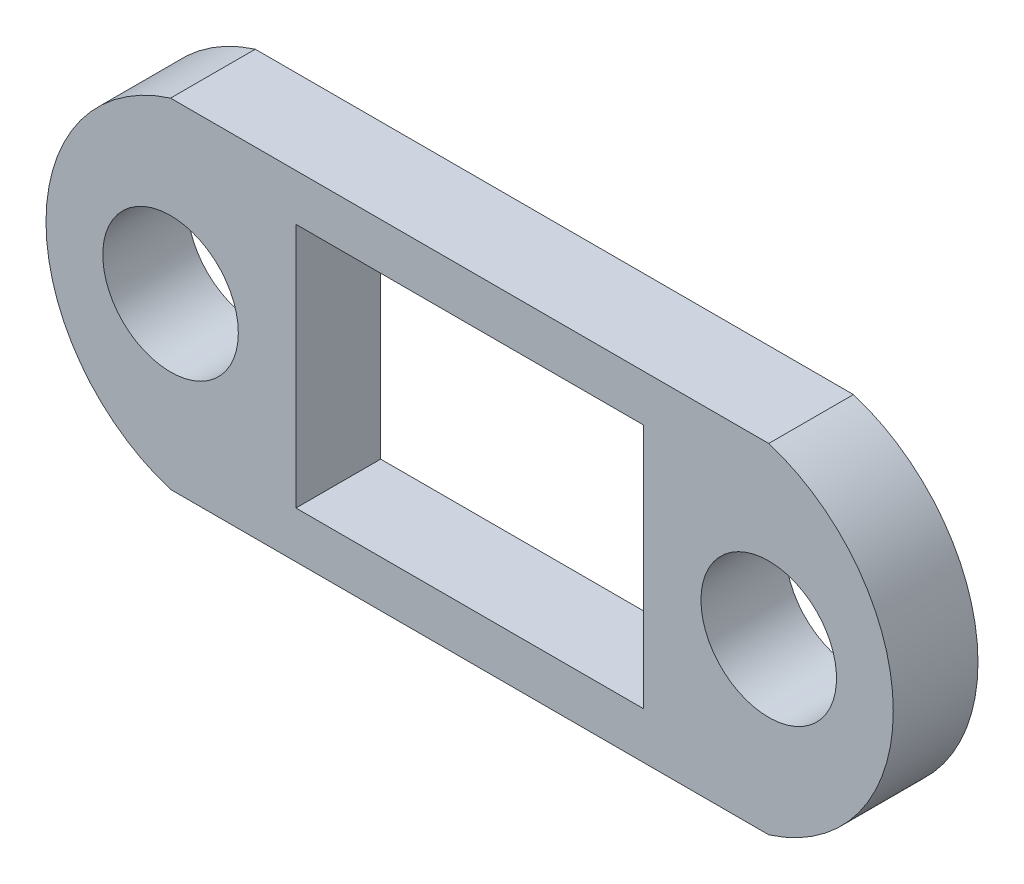
SolidWorks part; units mm, degrees
ref_plane "Front Plane" through (0, 0, 0) normal (0, 0, 1) x (1, 0, 0)
ref_plane "Top Plane" through (0, 0, 0) normal (0, 1, 0) x (1, 0, 0)
ref_plane "Right Plane" through (0, 0, 0) normal (1, 0, 0) x (0, 0, -1)
sketch "Sketch1" plane through (0, 0, 0) normal (0, 0, 1) x (1, 0, 0)
  line L0 (0, 3.425) -> (0, -3.425) construction
  line L1 (-4.925, -3.425) -> (4.925, -3.425)
  line L2 (-4.925, -3.425) -> (-4.925, 3.425)
  line L3 (-4.925, 3.425) -> (4.925, 3.425)
  line L4 (4.925, -3.425) -> (4.925, 3.425)
  line L5 (-4.925, -3.425) -> (4.925, 3.425) construction
  line L6 (-4.925, 3.425) -> (4.925, -3.425) construction
  line L7 (3.085, 4.125) -> (5.625, 4.125)
  line L8 (3.085, 4.125) -> (3.085, 2.725)
  line L9 (3.085, 2.725) -> (5.625, 2.725)
  line L10 (5.625, 4.125) -> (5.625, 2.725)
  line L11 (3.085, 4.125) -> (5.625, 2.725) construction
  line L12 (3.085, 2.725) -> (5.625, 4.125) construction
  line L13 (5.625, 2.725) -> (4.925, 2.725)
  line L14 (5.625, 2.725) -> (5.625, 3.425)
  line L15 (5.625, 3.425) -> (4.925, 3.425) construction
  line L16 (4.925, 2.725) -> (4.925, 3.425) construction
  line L17 (-4.925, 0) -> (4.925, 0) construction
  line L18 (-5.625, 4.125) -> (-5.625, 2.725)
  line L19 (-3.085, 4.125) -> (-5.625, 4.125)
  line L20 (-3.085, 4.125) -> (-3.085, 2.725)
  line L21 (-3.085, 2.725) -> (-5.625, 2.725)
  line L22 (5.625, -4.125) -> (5.625, -2.725)
  line L23 (3.085, -4.125) -> (5.625, -4.125)
  line L24 (3.085, -4.125) -> (3.085, -2.725)
  line L25 (3.085, -2.725) -> (5.625, -2.725)
  line L26 (-3.085, -2.725) -> (-5.625, -2.725)
  line L27 (-3.085, -4.125) -> (-3.085, -2.725)
  line L28 (-3.085, -4.125) -> (-5.625, -4.125)
  line L29 (-5.625, -4.125) -> (-5.625, -2.725)
  point P0 (0, 0)
  point P5 (4.355, 3.425)
  dimension "D1" = 6.85
  dimension "D2" = 9.85
  dimension "D3" = 1.4
  dimension "D4" = 2.54
  dimension "D5" = 0.7
sketch "Sketch2" plane through (0, 0, 0) normal (0, 0, 1) x (1, 0, 0)
  line L0 (3.085, 4.125) -> (5.625, 4.125) construction
  line L1 (5.625, 4.125) -> (5.625, 2.725) construction
  line L2 (5.625, -4.125) -> (5.625, -2.725) construction
  line L3 (3.085, -4.125) -> (5.625, -4.125) construction
  line L4 (-3.085, -4.125) -> (-5.625, -4.125) construction
  line L5 (-5.625, -4.125) -> (-5.625, -2.725) construction
  line L6 (-5.625, 4.125) -> (-5.625, 2.725) construction
  line L7 (-3.085, 4.125) -> (-5.625, 4.125) construction
  line L8 (-4.925, -3.425) -> (4.925, -3.425) construction
  line L9 (4.925, -3.425) -> (4.925, 3.425) construction
  line L10 (-4.925, 3.425) -> (4.925, 3.425) construction
  line L11 (-4.925, -3.425) -> (-4.925, 3.425) construction
  line L12 (3.085, 4.125) -> (5.625, 4.125) construction
  line L13 (5.625, 4.125) -> (5.625, 2.725) construction
  line L14 (5.625, -4.125) -> (5.625, -2.725) construction
  line L15 (3.085, -4.125) -> (5.625, -4.125) construction
  line L16 (-3.085, -4.125) -> (-5.625, -4.125) construction
  line L17 (-5.625, -4.125) -> (-5.625, -2.725) construction
  line L18 (-5.625, 4.125) -> (-5.625, 2.725) construction
  line L19 (-3.085, 4.125) -> (-5.625, 4.125) construction
  line L20 (-3.085, -3.425) -> (3.085, -3.425) construction
  line L21 (4.925, -2.725) -> (4.925, 2.725) construction
  line L22 (-3.085, 3.425) -> (3.085, 3.425) construction
  line L23 (-4.925, -2.725) -> (-4.925, 2.725) construction
  line L24 (-5.625, 2.725) -> (-4.925, 2.725) construction
  line L25 (-5.625, -2.725) -> (-4.925, -2.725) construction
  line L26 (-3.085, -2.725) -> (-5.625, -2.725) construction
  line L27 (-3.085, -4.125) -> (-3.085, -3.425) construction
  line L28 (-3.085, -4.125) -> (-3.085, -2.725) construction
  line L29 (3.085, -4.125) -> (3.085, -3.425) construction
  line L30 (5.625, -2.725) -> (4.925, -2.725) construction
  line L31 (3.085, 4.125) -> (3.085, 3.425) construction
  line L32 (3.085, 4.125) -> (3.085, 2.725) construction
  line L33 (5.625, 2.725) -> (4.925, 2.725) construction
  line L34 (-3.085, 4.125) -> (-3.085, 3.425) construction
  line L55 (-4.925, 3.425) -> (4.925, -3.425) construction
  line L56 (-8.825, -5.0001) -> (12.5, -5.0001) construction
  line L57 (-12.4999, -5) -> (-12.4999, 5) construction
  line L58 (-12.4999, 5) -> (12.5, 5) construction
  line L59 (12.5, -5.0001) -> (12.5, 5) construction
  line L60 (-12.5, -5) -> (12.5, 5) construction
  line L61 (-12.4999, 5) -> (12.5, -5.0001) construction
  line L62 (-8.825, 5) -> (-8.825, -5.0001) construction
  line L63 (-8.825, -5.0001) -> (-12.5, -5) construction
  line L64 (-5.825, 4.325) -> (-5.825, 5) construction
  line L65 (0, 3.425) -> (0, -3.425) construction
  line L66 (0, 3.425) -> (0, -3.425) construction
  line L67 (-8.825, 5) -> (8.825, 5)
  line L68 (-8.825, -5.0001) -> (8.825, -5.0001)
  line L69 (-5.125, -2.725) -> (-5.125, 2.725)
  line L70 (-3.085, 3.625) -> (3.085, 3.625)
  line L71 (5.125, -2.725) -> (5.125, 2.725)
  line L72 (-3.085, -3.625) -> (3.085, -3.625)
  line L73 (-5.125, -2.725) -> (-5.125, -3.625)
  line L74 (-5.125, -3.625) -> (-3.085, -3.625)
  line L75 (3.085, -3.625) -> (5.125, -3.625)
  line L76 (5.125, -3.625) -> (5.125, -2.725)
  line L77 (5.125, 2.725) -> (5.125, 3.625)
  line L78 (5.125, 3.625) -> (3.085, 3.625)
  line L79 (-3.085, 3.625) -> (-5.125, 3.625)
  line L80 (-5.125, 3.625) -> (-5.125, 2.725)
  arc A0 (-8.825, 5) -> (-8.825, -5.0001) centre (-7.261, 0) ccw
  arc A1 (8.825, 5) -> (8.825, -5.0001) centre (7.261, 0) cw
  circle A2 centre (-8.825, 0) radius 2
  circle A3 centre (8.825, 0) radius 2
  point P51 (0, 0)
  dimension "D5" = 4
  dimension "D1" = 0.2
  dimension "D2" = 10
  dimension "D3" = 25
  dimension "D4" = 0.2
extrude "Boss-Extrude1" add sketch "Sketch2" along normal blind 2.5
